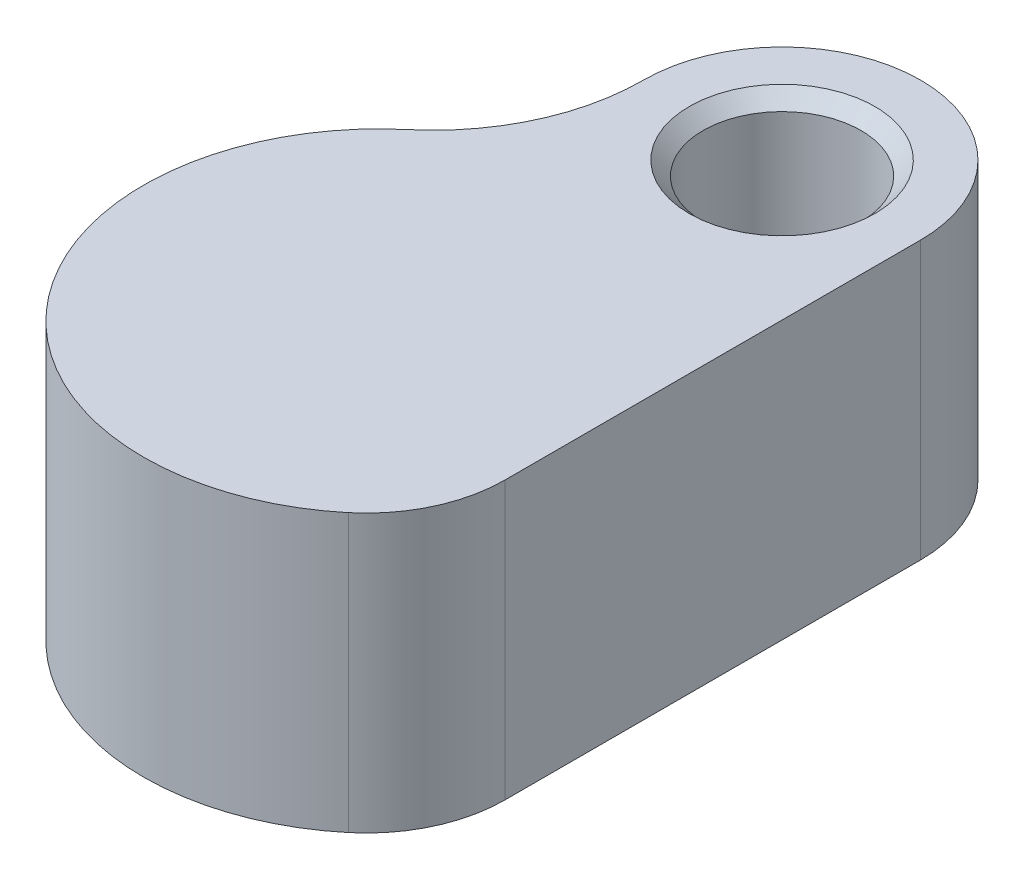
SolidWorks part; units mm, degrees
ref_plane "Front Plane" through (0, 0, 0) normal (0, 0, 1) x (1, 0, 0)
ref_plane "Top Plane" through (0, 0, 0) normal (0, 1, 0) x (1, 0, 0)
ref_plane "Right Plane" through (0, 0, 0) normal (1, 0, 0) x (0, 0, -1)
sketch "Sketch2" plane through (0, 0, 0) normal (0, 1, 0) x (1, 0, 0)
  line L1 (0, 0) -> (0, -15) construction
  line L3 (5, -15) -> (5, 0)
  circle A0 centre (0, 0) radius 1.6
  circle A1 centre (0, 0) radius 2.85
  circle A2 centre (0, 0) radius 5
  circle A3 centre (0, -15) radius 5
  arc A4 (3.1978, -18.8437) -> (-3.1765, -3.8613) centre (-2.2385, -12.3094) cw
  arc A5 (-7.7035, -5.7991) -> (-5, 0) centre (-12.5715, 0) ccw
  dimension "D1" = 3.2
  dimension "D2" = 5.7
  dimension "D3" = 10
  dimension "D5" = 10
  dimension "D6" = 8.5
  dimension "D4" = 15
extrude "Boss-Extrude1" add sketch "Sketch2" along normal blind 8
chamfer "Chamfer1" distance 0.5 angle 45 1 edges at (0, 8, 2.85)
sketch "Sketch4" plane through (0, 0, 0) normal (0, 1, 0) x (1, 0, 0)
  line L1 (5, -15) -> (5, 0)
  line L2 (5, -15) -> (5, 0)
  circle A0 centre (0, 0) radius 1.6
  arc A4 (-7.7035, -5.7991) -> (3.1978, -18.8437) centre (-2.2385, -12.3094) ccw
  arc A5 (-7.7035, -5.7991) -> (3.1978, -18.8437) centre (-2.2385, -12.3094) ccw
  arc A6 (5, 0) -> (-5, 0) centre (0, 0) ccw
  arc A7 (3.1978, -18.8437) -> (5, -15) centre (0, -15) ccw
  arc A10 (5, 0) -> (-5, 0) centre (0, 0) ccw
  arc A11 (3.1978, -18.8437) -> (5, -15) centre (0, -15) ccw
  arc A13 (-7.7035, -5.7991) -> (-5, 0) centre (-12.5715, 0) ccw
  arc A14 (-7.7035, -5.7991) -> (-5, 0) centre (-12.5715, 0) ccw
  dimension "D2" = 3.2
  dimension "D1" = 0
extrude "Boss-Extrude3" add sketch "Sketch4" against normal blind 2
